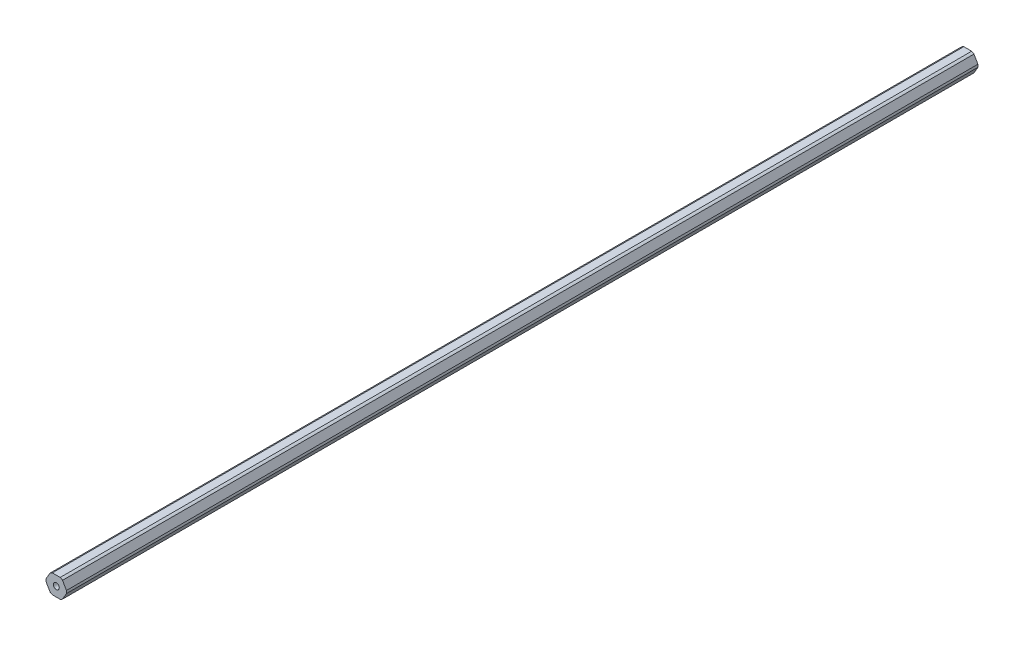
SolidWorks part; units mm, degrees
material "6061-T6 (SS)"
ref_plane "Front Plane" through (0, 0, 0) normal (0, 0, 1) x (1, 0, 0)
ref_plane "Top Plane" through (0, 0, 0) normal (0, 1, 0) x (1, 0, 0)
ref_plane "Right Plane" through (0, 0, 0) normal (1, 0, 0) x (0, 0, -1)
sketch "Sketch1" plane through (0, 0, 0) normal (0, 0, 1) x (1, 0, 0)
  line L1 (3.6662, 6.35) -> (-3.6662, 6.35)
  line L2 (-3.6662, 6.35) -> (-7.3323, 0)
  line L3 (-7.3323, 0) -> (-3.6662, -6.35)
  line L4 (-3.6662, -6.35) -> (3.6662, -6.35)
  line L5 (3.6662, -6.35) -> (7.3323, 0)
  line L6 (7.3323, 0) -> (3.6662, 6.35)
  circle A0 centre (0, 0) radius 6.35 construction
  circle A1 centre (0, 0) radius 6.875
  circle A2 centre (0, 0) radius 2
  point P1 (0, 6.35)
  dimension "D2" = 13.75
  dimension "D3" = 4
  dimension "D1" = 12.7
extrude "Boss-Extrude1" add sketch "Sketch1" along normal blind 609.6 contours L6 A1 L1 L2 L3 L4 L5 A2
equation "\"D2@Sketch1\"=13.750000mm"
equation "\"D3@Sketch1\"=4mm"
